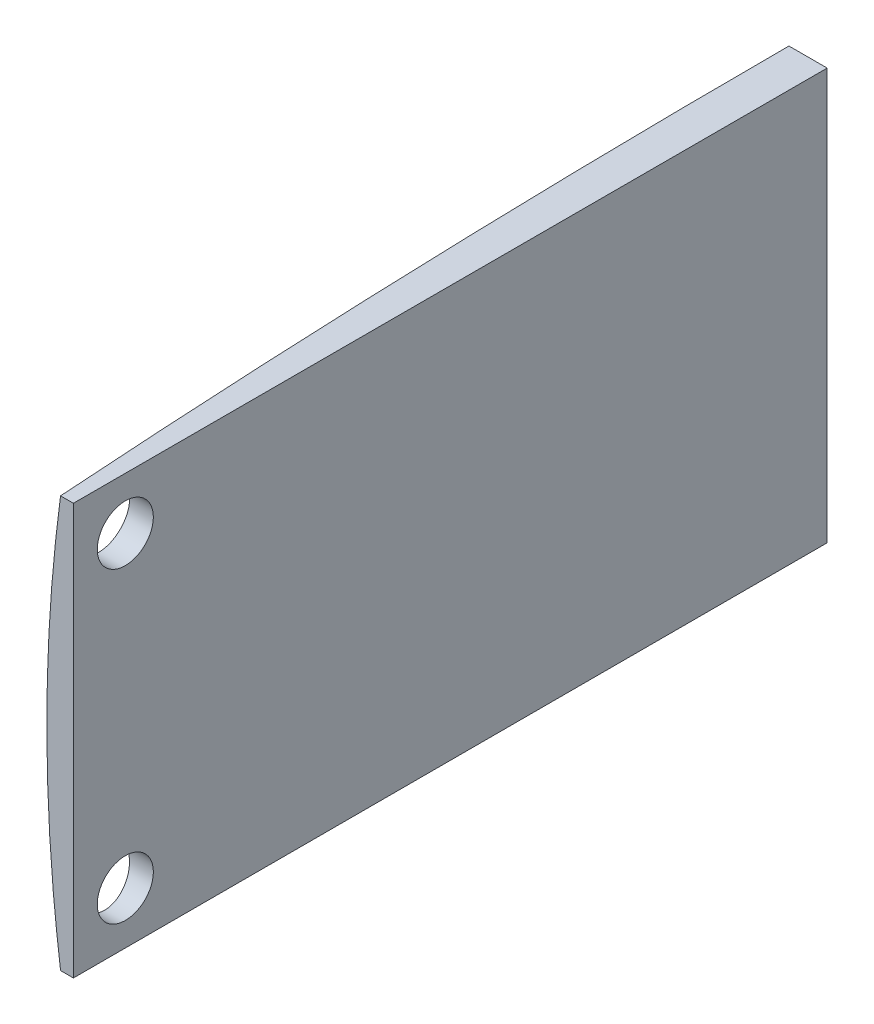
SolidWorks part; units mm, degrees
material "Nylon 101"
ref_plane "Front Plane" through (0, 0, 0) normal (0, 0, 1) x (1, 0, 0)
ref_plane "Top Plane" through (0, 0, 0) normal (0, 1, 0) x (1, 0, 0)
ref_plane "Right Plane" through (0, 0, 0) normal (1, 0, 0) x (0, 0, -1)
sketch "Sketch1" plane through (0, 0, 0) normal (0, 0, 1) x (1, 0, 0)
  line L0 (0, 0) -> (1372.87, 0) construction
  line L1 (1372.87, -509.27) -> (1372.87, 509.27)
  ellipse E0 centre (1372.87, 0) end of major axis (0, 0) minor radius 509.27 (1372.87, 509.27) -> (1372.87, -509.27) ccw
  point P4 (1372.87, 0)
  dimension "D1" = 1018.54
  dimension "D2" = 1372.87
revolve "Revolve1" add sketch "Sketch1" angle 360 about L1
sketch "Sketch2" plane through (0, 0, 0) normal (1, 0, 0) x (0, 0, -1)
  line L1 (92.202, 25.146) -> (-92.202, 25.146)
  line L2 (92.202, 25.146) -> (92.202, -25.146)
  line L3 (92.202, -25.146) -> (-92.202, -25.146)
  line L4 (-92.202, 25.146) -> (-92.202, -25.146)
  line L5 (92.202, 25.146) -> (-92.202, -25.146) construction
  line L6 (92.202, -25.146) -> (-92.202, 25.146) construction
  point P0 (0, 0)
  dimension "D1" = 184.404
  dimension "D2" = 50.292
extrude "Cut-Extrude2" cut sketch "Sketch2" against normal through all and the other way through all flip side to cut contours L1 L4 L3 L2
sketch "Sketch3" plane through (0, 0, 0) normal (1, 0, 0) x (0, 0, -1)
  line L1 (92.202, 25.146) -> (-92.202, 25.146)
  line L2 (92.202, 25.146) -> (92.202, -25.146)
  line L3 (92.202, -25.146) -> (-92.202, -25.146)
  line L4 (-92.202, 25.146) -> (-92.202, -25.146)
  line L5 (92.202, 25.146) -> (-92.202, -25.146) construction
  line L6 (92.202, -25.146) -> (-92.202, 25.146) construction
  point P0 (0, 0)
extrude "Cut-Extrude3" cut sketch "Sketch3" along normal through all from offset 6.35
sketch "Sketch4" plane through (6.35, 0, 0) normal (1, 0, 0) x (0, 0, -1)
  line L0 (92.202, 25.146) -> (-92.202, 25.146) construction
  line L1 (-92.202, 25.146) -> (-92.202, -25.146) construction
  line L2 (92.202, -25.146) -> (92.202, 25.146) construction
  line L3 (-92.202, -25.146) -> (92.202, -25.146) construction
  circle A0 centre (-85.852, 18.796) radius 3.429
  circle A1 centre (-85.852, -18.796) radius 3.429
  circle A2 centre (85.852, -18.796) radius 3.429
  circle A3 centre (85.852, 18.796) radius 3.429
  dimension "D1" = 6.35
  dimension "D5" = 6.858
  dimension "D2" = 6.35
  dimension "D3" = 6.35
  dimension "D4" = 6.35
extrude "Cut-Extrude4" cut sketch "Sketch4" against normal through all
sketch "Sketch5" plane through (0, 0, 0) normal (0, 0, 1) x (1, 0, 0)
  line L1 (-45.5632, -78.759) -> (23.5723, -78.759)
  line L2 (-45.5632, -78.759) -> (-45.5632, 28.6133)
  line L3 (-45.5632, 28.6133) -> (23.5723, 28.6133)
  line L4 (23.5723, -78.759) -> (23.5723, 28.6133)
  line L5 (-45.5632, -78.759) -> (23.5723, 28.6133) construction
  line L6 (-45.5632, 28.6133) -> (23.5723, -78.759) construction
  point P0 (-10.9955, -25.0729)
extrude "Cut-Extrude5" cut sketch "Sketch5" against normal through all contours L2 L3 L4 L1
